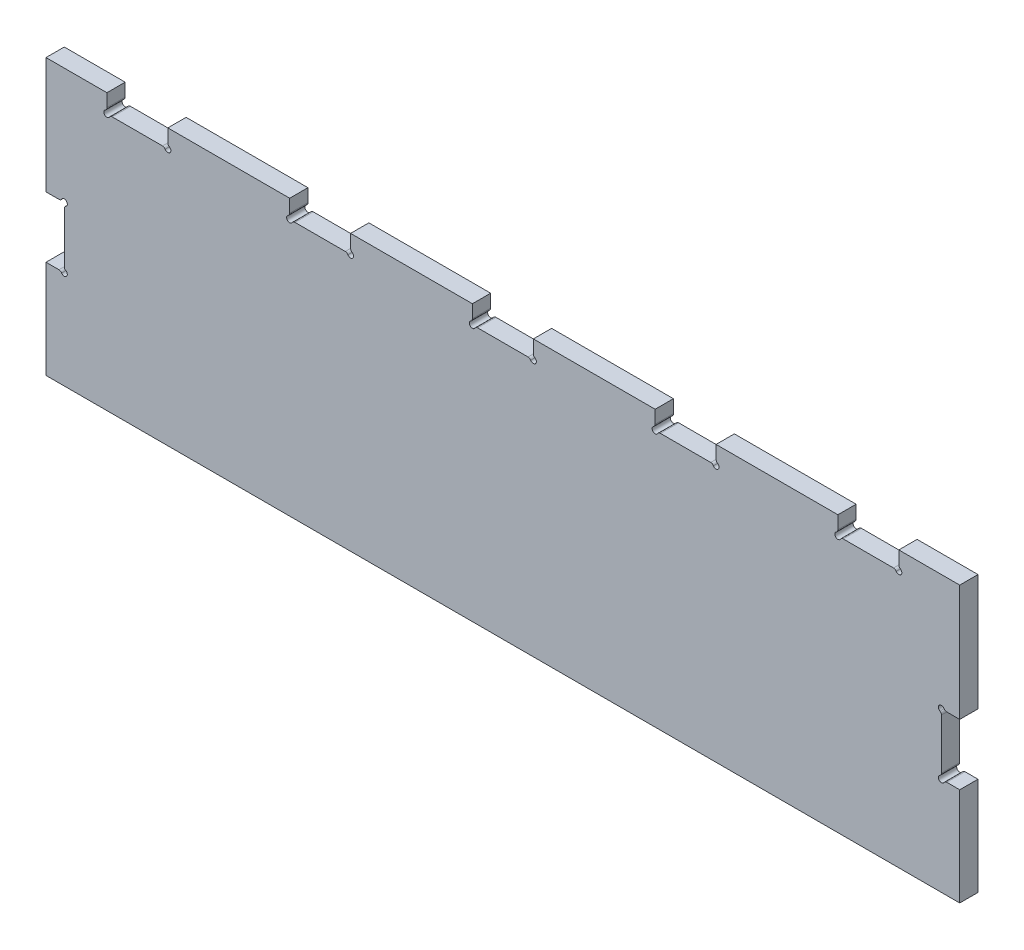
SolidWorks part; units mm, degrees
ref_plane "Front Plane" through (0, 0, 0) normal (0, 0, 1) x (1, 0, 0)
ref_plane "Top Plane" through (0, 0, 0) normal (0, 1, 0) x (1, 0, 0)
ref_plane "Right Plane" through (0, 0, 0) normal (1, 0, 0) x (0, 0, -1)
sketch "Sketch1" plane through (0, 0, 0) normal (0, 0, 1) x (1, 0, 0)
  line L2 (65, -3) -> (65, 0)
  line L4 (55, -3) -> (55, 0)
  line L6 (35, -3) -> (35, 0)
  line L8 (25, -3) -> (25, 0)
  line L10 (5, -3) -> (5, 0)
  line L12 (-5, -3) -> (-5, 0)
  line L14 (-25, -3) -> (-25, 0)
  line L16 (-35, -3) -> (-35, 0)
  line L18 (-55, -3) -> (-55, 0)
  line L20 (-65, -3) -> (-65, 0)
  line L22 (-75, -45.2) -> (75, -45.2)
  line L28 (0, 0) -> (0, -60.0812) construction
  line L36 (-65, 0) -> (-75, 0)
  line L39 (-65, -3) -> (-55, -3)
  line L40 (-55, 0) -> (-35, 0)
  line L41 (-35, -3) -> (-25, -3)
  line L42 (-25, 0) -> (-5, 0)
  line L43 (-5, -3) -> (5, -3)
  line L44 (5, 0) -> (25, 0)
  line L45 (25, -3) -> (35, -3)
  line L46 (35, 0) -> (55, 0)
  line L47 (55, -3) -> (65, -3)
  line L48 (65, 0) -> (75, 0)
  line L49 (-75, -45.2) -> (-75, -24.1) construction
  line L51 (-75, -24.1) -> (-72, -24.1) construction
  line L53 (-72, -29.1) -> (-72, -19.1)
  line L55 (-72, -29.1) -> (-75, -29.1)
  line L57 (-72, -19.1) -> (-75, -19.1)
  line L59 (-75, 0) -> (-75, -19.1)
  line L60 (-75, -29.1) -> (-75, -45.2)
  line L61 (75, -29.1) -> (75, -45.2)
  line L62 (72, -29.1) -> (75, -29.1)
  line L63 (72, -29.1) -> (72, -19.1)
  line L64 (72, -19.1) -> (75, -19.1)
  line L65 (75, 0) -> (75, -19.1)
  point P29 (-72, -24.1)
  dimension "D3" = 150
  dimension "D4" = 10
  dimension "D5" = 20
  dimension "D6" = 10
  dimension "D7" = 20
  dimension "D8" = 10
  dimension "D9" = 20
  dimension "D10" = 10
  dimension "D11" = 20
  dimension "D12" = 10
  dimension "D14" = 10
  dimension "D15" = 45.2
  dimension "D16" = 3
  dimension "D17" = 3
  dimension "D18" = 3
  dimension "D19" = 3
  dimension "D20" = 3
  dimension "D21" = 3
  dimension "D22" = 3
  dimension "D23" = 3
  dimension "D24" = 3
  dimension "D26" = 21.1
  dimension "D27" = 3
  dimension "D28" = 10
  dimension "D29" = 3
extrude "Boss-Extrude1" add sketch "Sketch1" along normal mid plane 3
sketch "Sketch2" plane through (0, 0, 1.5) normal (0, 0, 1) x (1, 0, 0)
  circle A10 centre (-72, -29.1) radius 0.5
  circle A11 centre (-72, -19.1) radius 0.5
  circle A12 centre (-65, -3) radius 0.5
  circle A13 centre (-55, -3) radius 0.5
  circle A14 centre (-35, -3) radius 0.5
  circle A15 centre (-25, -3) radius 0.5
  circle A16 centre (-5, -3) radius 0.5
  circle A17 centre (5, -3) radius 0.5
  circle A18 centre (25, -3) radius 0.5
  circle A19 centre (35, -3) radius 0.5
  circle A20 centre (55, -3) radius 0.5
  circle A21 centre (65, -3) radius 0.5
  circle A22 centre (72, -19.1) radius 0.5
  circle A23 centre (72, -29.1) radius 0.5
  dimension "D1" = 1
  dimension "D2" = 1
extrude "Cut-Extrude1" cut sketch "Sketch2" against normal through all
fillet "Fillet1" radius 0.5 28 edges at (72.5, -19.1, 0) (72, -19.6, 0) (72.5, -29.1, 0) (72, -28.6, 0) (65, -2.5, 0) (64.5, -3, 0) (55, -2.5, 0) (55.5, -3, 0) (35, -2.5, 0) (34.5, -3, 0) (25, -2.5, 0) (25.5, -3, 0) (4.5, -3, 0) (5, -2.5, 0) (-4.5, -3, 0) (-5, -2.5, 0) (-25, -2.5, 0) (-25.5, -3, 0) (-35, -2.5, 0) (-34.5, -3, 0) (-55, -2.5, 0) (-55.5, -3, 0) (-64.5, -3, 0) (-65, -2.5, 0) (-72, -19.6, 0) (-72.5, -19.1, 0) (-72.5, -29.1, 0) (-72, -28.6, 0)
